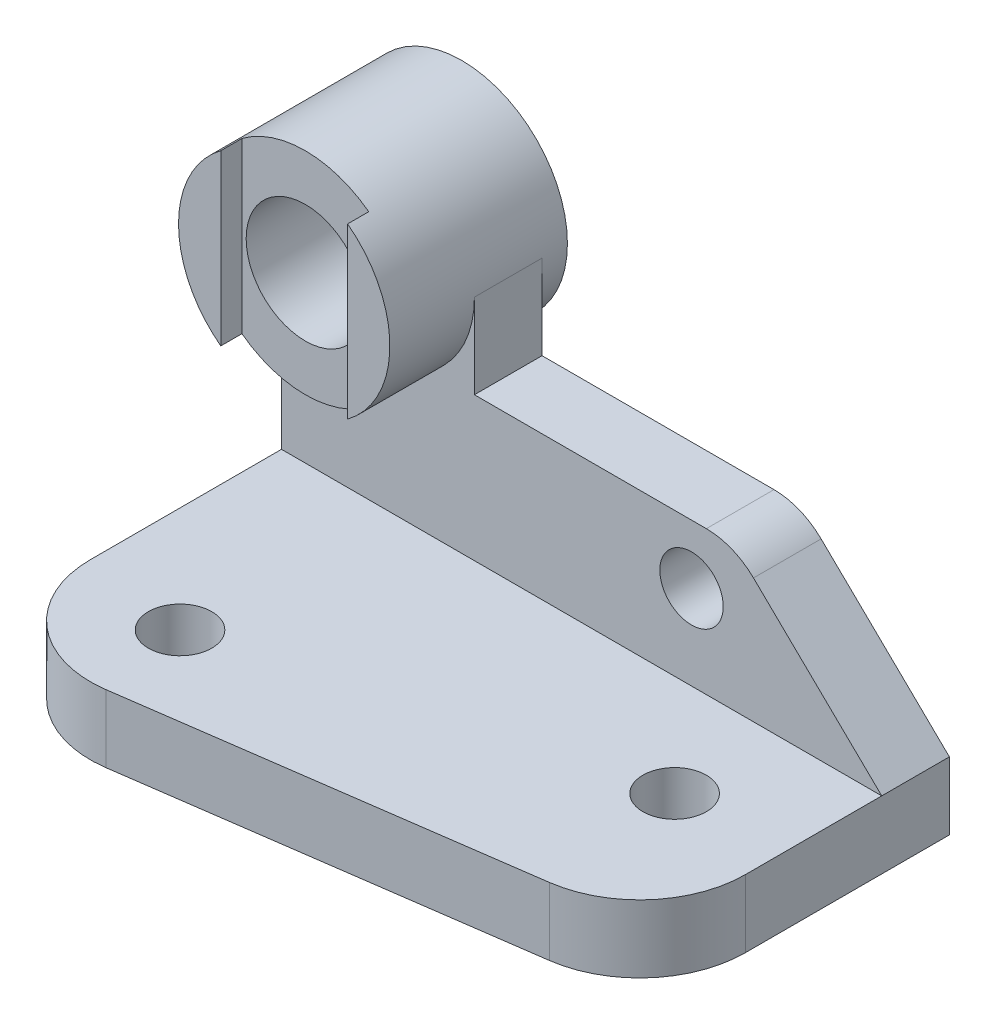
SolidWorks part; units mm, degrees
ref_plane "Front Plane" through (0, 0, 0) normal (0, 0, 1) x (1, 0, 0)
ref_plane "Top Plane" through (0, 0, 0) normal (0, 1, 0) x (1, 0, 0)
ref_plane "Right Plane" through (0, 0, 0) normal (1, 0, 0) x (0, 0, -1)
sketch "Sketch1" plane through (0, 0, 0) normal (0, 1, 0) x (1, 0, 0)
  line L0 (0, 0) -> (142, 0)
  line L1 (142, 0) -> (142, -70)
  line L2 (142, -70) -> (0, -90)
  line L3 (0, -90) -> (0, 0)
  dimension "D1" = 142
  dimension "D2" = 90
  dimension "D3" = 70
extrude "Boss-Extrude1" add sketch "Sketch1" along normal blind 16
fillet "Fillet1" radius 25 2 edges at (142, 8, 70) (0, 8, 90)
sketch "Sketch2" plane through (0, 16, 0) normal (0, 1, 0) x (1, 0, 0)
  line L0 (142, 0) -> (0, 0) construction
  line L1 (142, -48.2744) -> (142, 0) construction
  circle A0 centre (25, -65) radius 7.5
  circle A1 centre (117, -40) radius 7.5
  dimension "D1" = 40
  dimension "D5" = 15
  dimension "D2" = 25
  dimension "D3" = 25
  dimension "D4" = 92
extrude "Cut-Extrude1" cut sketch "Sketch2" against normal through all
sketch "Sketch3" plane through (0, 0, 0) normal (0, 0, -1) x (-1, 0, 0)
  line L0 (-142, 0) -> (0, 0) construction
  circle A0 centre (-20.64, 70) radius 25
  circle A1 centre (-20.64, 70) radius 14
  point P6 (-17.026, 43.2641)
  point P7 (-18.9955, 78.0576)
  dimension "D1" = 28
  dimension "D2" = 50
  dimension "D3" = 121.36
  dimension "D4" = 70
extrude "Boss-Extrude2" add sketch "Sketch3" along normal blind 6 and the other way blind 36 separate body
sketch "Sketch4" plane through (0, 0, 0) normal (0, 0, 1) x (1, 0, 0)
  line L0 (142, 16) -> (111.6566, 45.4765)
  line L1 (100.508, 50) -> (45.64, 50)
  line L2 (45.64, 50) -> (45.64, 70)
  line L3 (142, 16) -> (0, 16)
  line L4 (0, 16) -> (0, 55.8936)
  line L5 (28.4867, 0) -> (120.4867, 0) construction
  circle A0 centre (20.64, 70) radius 25 construction
  arc A1 (0, 55.8936) -> (45.64, 70) centre (20.64, 70) ccw
  arc A2 (111.6566, 45.4765) -> (100.508, 50) centre (100.508, 34) ccw
  point P15 (107, 50)
  dimension "D3" = 16
  dimension "D1" = 35
  dimension "D2" = 50
extrude "Boss-Extrude3" add sketch "Sketch4" along normal blind 16
sketch "Sketch5" plane through (0, 0, 16) normal (0, 0, 1) x (1, 0, 0)
  line L0 (142, 16) -> (142, 0) construction
  line L1 (0, 16) -> (142, 16) construction
  circle A0 centre (97, 36) radius 7.5
  dimension "D1" = 15
  dimension "D2" = 45
  dimension "D3" = 20
extrude "Cut-Extrude2" cut sketch "Sketch5" against normal through all
sketch "Sketch6" plane through (0, 0, 36) normal (0, 0, 1) x (1, 0, 0)
  line L0 (20.64, 95) -> (20.64, 45) construction
  line L2 (5.64, 100) -> (35.64, 100)
  line L3 (5.64, 100) -> (5.64, 40)
  line L4 (5.64, 40) -> (35.64, 40)
  line L5 (35.64, 100) -> (35.64, 40)
  line L6 (5.64, 100) -> (35.64, 40) construction
  line L7 (5.64, 40) -> (35.64, 100) construction
  circle A0 centre (20.64, 70) radius 25 construction
  arc A1 (0, 55.8936) -> (45.64, 70) centre (20.64, 70) ccw construction
  point P8 (20.64, 70)
  dimension "D1" = 60
  dimension "D2" = 30
extrude "Cut-Extrude3" cut sketch "Sketch6" against normal blind 5
